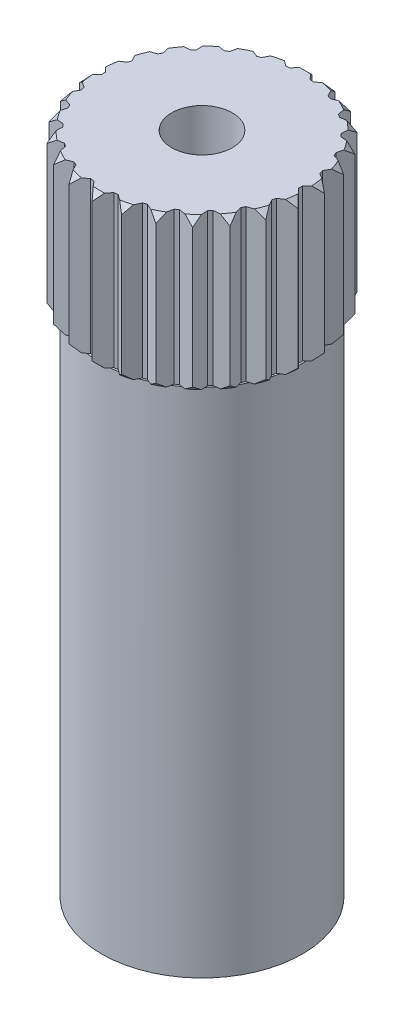
SolidWorks part; units mm, degrees
material "Brass"
ref_plane "Front Plane" through (0, 0, 0) normal (0, 0, 1) x (1, 0, 0)
ref_plane "Top Plane" through (0, 0, 0) normal (0, 1, 0) x (1, 0, 0)
ref_plane "Right Plane" through (0, 0, 0) normal (1, 0, 0) x (0, 0, -1)
sketch "Sketch12" plane through (0, 0, 0) normal (0, 1, 0) x (1, 0, 0)
  circle A0 centre (0, 0) radius 2.9
  dimension "D1" = 5.8
extrude "Boss-Extrude4" add sketch "Sketch12" along normal blind 13.5 separate body
sketch "Sketch13" plane through (0, 13.5, 0) normal (0, 1, 0) x (1, 0, 0)
  circle A2 centre (0, 0) radius 2.6
  circle A3 centre (0, 0) radius 2.9 construction
  dimension "D1" = 0.3
extrude "Boss-Extrude5" add sketch "Sketch13" along normal blind 4
sketch "Sketch14" plane through (0, 17.5, 0) normal (0, 1, 0) x (1, 0, 0)
  line L0 (0, 2.6) -> (0, 2.9) construction
  line L1 (0, 2.9) -> (-0.2629, 2.5867)
  line L2 (0, 2.9) -> (0.2629, 2.5867)
  line L3 (-0.2629, 2.5867) -> (0.2629, 2.5867) construction
  circle A0 centre (0, 0) radius 2.9 construction
  circle A1 centre (0, 0) radius 2.6
  arc A2 (0.2629, 2.5867) -> (-0.2629, 2.5867) centre (0, 0) ccw
  dimension "D2" = 80
  dimension "D3" = 0.5258
  dimension "D4" = 0.3
  dimension "D1" = 0
extrude "Boss-Extrude6" add sketch "Sketch14" against normal up to body separate body
pattern_circular "CirPattern1" count 26 over 360 about axis through (0, 0, 0) along (0, 1, 0) of "Boss-Extrude6"
sketch "Sketch15" plane through (0, 0, 0) normal (1, 0, 0) x (0, 0, -1)
  line L0 (2.9, 17.3232) -> (2.9, 17.5)
  line L1 (2.9, 13.5) -> (2.9, 17.5) construction
  line L2 (2.9, 17.5) -> (2.7232, 17.5)
  line L3 (2.1682, 17.5) -> (2.5678, 17.5) construction
  line L4 (2.7232, 17.5) -> (2.9, 17.3232)
  dimension "D1" = 45
  dimension "D2" = 0.25
revolve "Cut-Revolve1" cut sketch "Sketch15" angle 360 about axis through (0, 17.5, 0) along (0, -1, 0)
sketch "Sketch16" plane through (0, 17.5, 0) normal (0, 1, 0) x (1, 0, 0)
  circle A0 centre (0, 0) radius 0.8
  dimension "D1" = 1.6
extrude "Cut-Extrude1" cut sketch "Sketch16" against normal blind 4
ref_plane "Plane1" through (-0.3638, 13.5, -2.5744) normal (-0.9902, 0, 0.1399) x (0.1399, 0, 0.9902)
sketch "Sketch17" plane through (0, 0, 0) normal (0, 0, 1) x (1, 0, 0)
  line L0 (2.9, 0) -> (2.65, 0)
  line L1 (-2.9, 0) -> (2.9, 0) construction
  line L2 (2.65, 0) -> (2.65, 13.5)
  line L3 (2.65, 13.5) -> (2.9, 13.5)
  line L4 (2.9, 13.5) -> (2.9, 0)
  line L5 (0, 0) -> (2.65, 0) construction
  line L6 (2.7115, 13.5) -> (2.3254, 13.5) construction
  dimension "D1" = 0.25
  dimension "D2" = 2.65
  dimension "D3" = 2.9
revolve "Cut-Revolve2" cut sketch "Sketch17" angle 360 about axis through (0, 13.5, 0) along (0, -1, 0)
ref_plane "Plane2" through (0, 15.5, 0) normal (0, 1, 0) x (1, 0, 0)
mirror "Mirror1" about plane through (0, 15.5, 0) normal (0, 1, 0) of "Cut-Revolve1"
move or copy body "Body-Move/Copy1" [suppressed] bodies to move or copy 125
move or copy body "Body-Move/Copy2" [suppressed] bodies to move or copy 126
